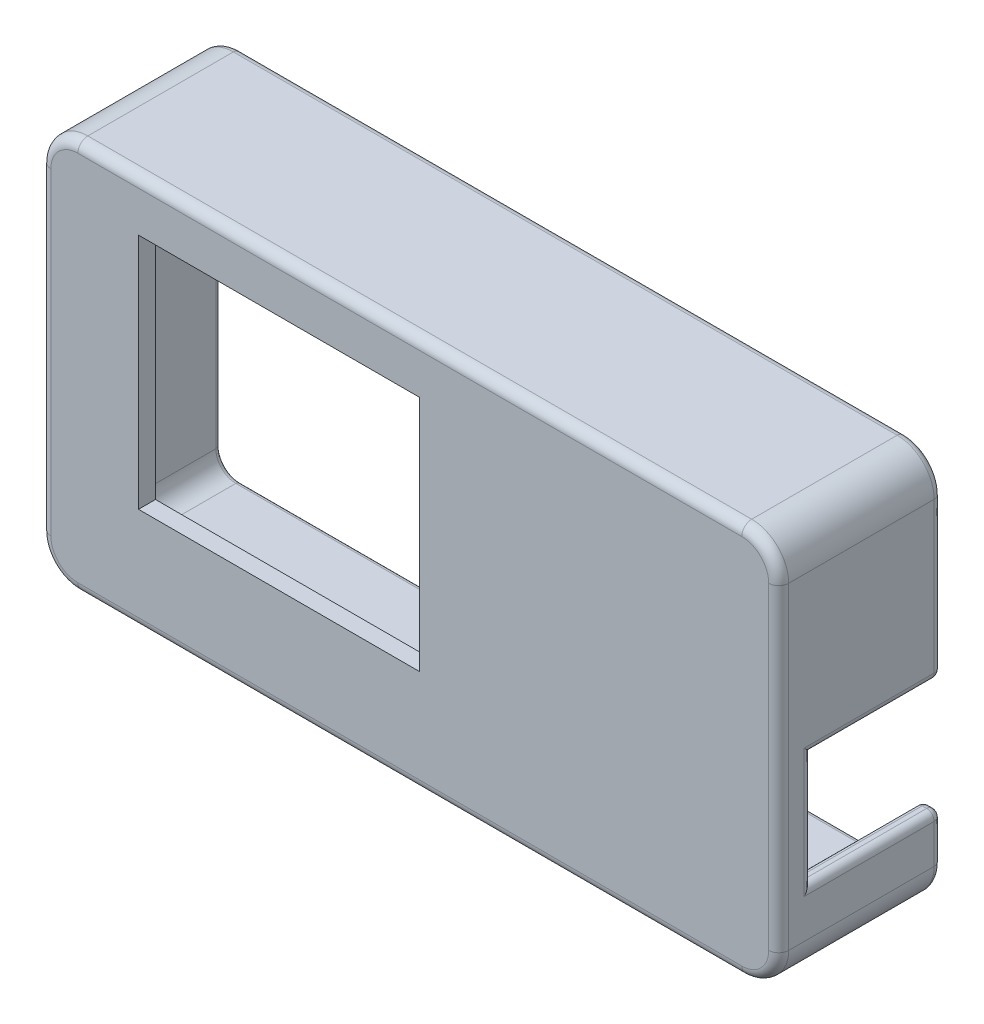
SolidWorks part; units mm, degrees
material "Alliage 1060"
ref_plane "Plan de face" through (0, 0, 0) normal (0, 0, 1) x (1, 0, 0)
ref_plane "Plan de dessus" through (0, 0, 0) normal (0, 1, 0) x (1, 0, 0)
ref_plane "Plan de droite" through (0, 0, 0) normal (1, 0, 0) x (0, 0, -1)
sketch "Esquisse1" plane through (0, 0, 0) normal (0, 0, 1) x (1, 0, 0)
  line L1 (2, 0) -> (68.4, 0)
  line L2 (0, 2) -> (0, 33.8)
  line L3 (2, 35.8) -> (68.4, 35.8)
  line L4 (70.4, 2) -> (70.4, 33.8)
  arc A0 (0, 33.8) -> (2, 35.8) centre (2, 33.8) cw
  arc A1 (2, 0) -> (0, 2) centre (2, 2) cw
  arc A2 (68.4, 0) -> (70.4, 2) centre (68.4, 2) ccw
  arc A3 (68.4, 35.8) -> (70.4, 33.8) centre (68.4, 33.8) cw
  point P7 (0, 35.8)
  point P10 (0, 0)
  point P13 (70.4, 0)
  point P16 (70.4, 35.8)
  dimension "D3" = 2
  dimension "D1" = 70.4
  dimension "D2" = 35.8
extrude "Boss.-Extru.1" add sketch "Esquisse1" along normal blind 14.6
shell "Coque1" thickness 1.7
sketch "Esquisse3" plane through (0, 0, 0) normal (0, 0, 1) x (1, 0, 0)
  line L0 (2, 37.5) -> (80.4448, 37.5) construction
  line L1 (68.4, 37.5) -> (2, 37.5) construction
  line L2 (72.1, 2) -> (72.1, 40.8551) construction
  line L3 (72.1, 2) -> (72.1, 33.8) construction
  line L4 (72.1, 37.5) -> (72.1, 29.1) construction
  line L5 (72.1, 37.5) -> (72.1, 18) construction
  line L6 (43.3533, -1.7) -> (83.41, -1.7) construction
  line L7 (2, -1.7) -> (68.4, -1.7) construction
  line L8 (72.1, -1.7) -> (72.1, 6.7) construction
  arc A0 (2, 37.5) -> (-1.7, 33.8) centre (2, 33.8) ccw construction
sketch "Esquisse4" plane through (0, 0, 0) normal (0, 0, -1) x (-1, 0, 0)
  line L0 (-53.8636, -1.7) -> (-84.4725, -1.7) construction
  line L1 (-2, -1.7) -> (-68.4, -1.7) construction
sketch "Esquisse7" plane through (0, 0, 0) normal (0, 0, -1) x (-1, 0, 0)
  line L0 (-70.4, 2) -> (-70.4, 33.8) construction
  line L1 (-72.1, 18) -> (-70.4, 18)
  line L2 (-72.1, 18) -> (-72.1, 6.6448)
  line L3 (-72.1, 6.6448) -> (-70.4, 6.6448)
  line L4 (-70.4, 18) -> (-70.4, 6.6448)
extrude "Enlèv. mat.-Extru.2" cut sketch "Esquisse7" against normal blind 13
fillet "Congé2" radius 0.75 2 edges at (71.25, 6.6448, 0) (71.25, 18, 0)
sketch "Esquisse8" plane through (0, 0, 0) normal (0, 0, 1) x (1, 0, 0)
  line L0 (-1.7, 15.2341) -> (-1.7, 41.1363) construction
  line L1 (-1.7, 33.8) -> (-1.7, 2) construction
  line L2 (29.4211, 37.5) -> (-6.2742, 37.5) construction
  line L3 (2, 37.5) -> (80.4448, 37.5) construction
  line L4 (-1.7, 37.5) -> (6.6, 37.5) construction
  line L5 (6.6, 37.5) -> (34.08, 37.5) construction
  line L6 (6.6, 37.5) -> (6.6, -16.0202) construction
  line L7 (6.6, 37.5) -> (34.08, 37.5) construction
  line L8 (34.08, 37.5) -> (34.08, -7.2909) construction
  line L9 (6.6, 37.5) -> (6.6, 34.5) construction
  line L10 (6.6, 34.5) -> (34.08, 34.5) construction
  line L11 (6.6, 34.5) -> (6.6, 5.5) construction
  line L12 (6.6, 5.5) -> (34.08, 5.5) construction
  line L14 (6.6, 34.5) -> (34.08, 34.5)
  line L15 (6.6, 34.5) -> (6.6, 5.5)
  line L16 (6.6, 5.5) -> (34.08, 5.5)
  line L17 (34.08, 34.5) -> (34.08, 5.5)
sketch "Esquisse9" plane through (0, 0, 16.3) normal (0, 0, 1) x (1, 0, 0)
  line L5 (8.0661, 32.4429) -> (36.187, 32.4429)
  line L6 (8.0661, 32.4429) -> (8.0661, 8.6903)
  line L7 (8.0661, 8.6903) -> (36.187, 8.6903)
  line L8 (36.187, 32.4429) -> (36.187, 8.6903)
extrude "Enlèv. mat.-Extru.3" cut sketch "Esquisse9" against normal blind 3
fillet "Congé4" radius 1 8 edges at (71.0163, 36.4163, 16.3) (72.1, 17.9, 16.3) (71.0163, -0.6163, 16.3) (35.2, -1.7, 16.3) (-0.6163, -0.6163, 16.3) (-1.7, 17.9, 16.3) (-0.6163, 36.4163, 16.3) (35.2, 37.5, 16.3)
fillet "Congé5" radius 0.75 14 edges at (72.1, 3.9474, 0) (71.0163, -0.6163, 0) (35.2, -1.7, 0) (-0.6163, -0.6163, 0) (-1.7, 17.9, 0) (-0.6163, 36.4163, 0) (35.2, 37.5, 0) (71.0163, 36.4163, 0) (72.1, 26.275, 0) (72.1, 6.4252, 0.2197) (72.1, 18.2197, 0.2197) (72.1, 6.6448, 6.875) (72.1, 12.3224, 13) (72.1, 18, 6.875)
fillet "Congé6" radius 0.5 13 edges at (70.4, 18, 6.875) (70.4, 18.2197, 0.2197) (70.4, 6.6448, 6.875) (70.4, 6.4252, 0.2197) (70.4, 3.9474, 0) (69.8142, 0.5858, 0) (35.2, 0, 0) (0.5858, 0.5858, 0) (0, 17.9, 0) (0.5858, 35.2142, 0) (35.2, 35.8, 0) (69.8142, 35.2142, 0) (70.4, 26.275, 0)
